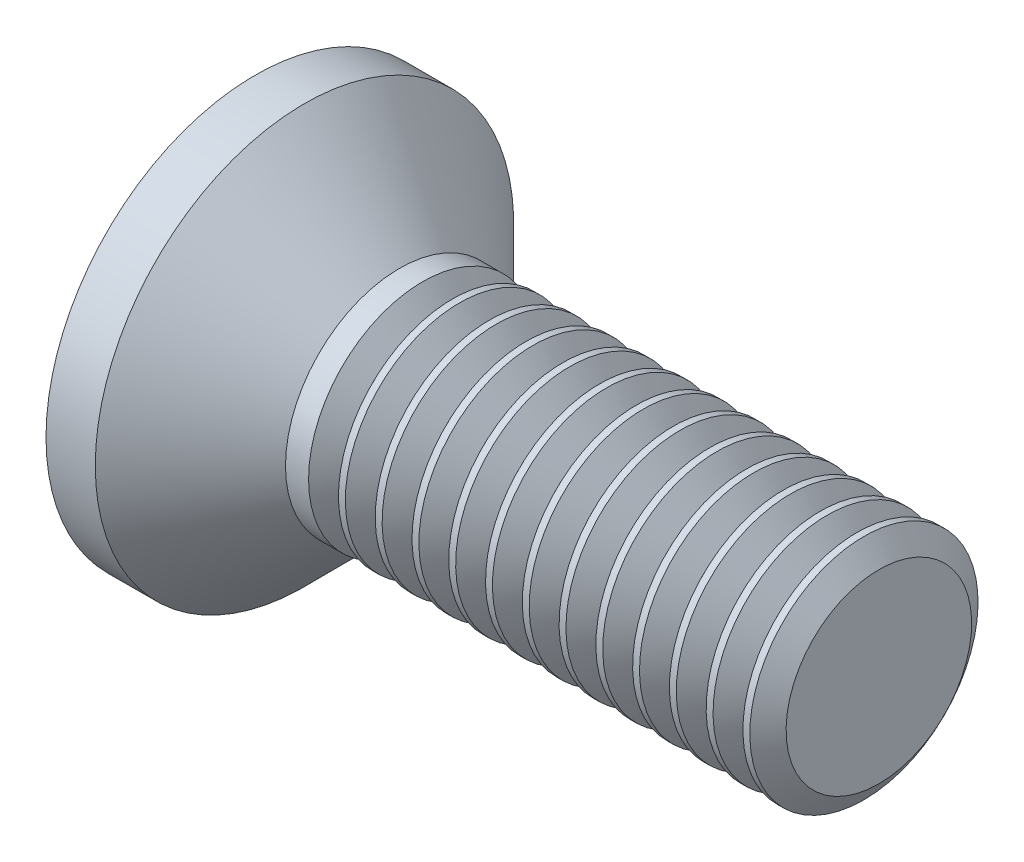
SolidWorks part; units mm, degrees
revolve "Base-Revolve" add sketch "BodySke" angle 360 about L4
sketch "BodySke" plane through (0, 0, 0) normal (0, 0, 1) x (1, 0, 0)
  line L0 (0, 0) -> (8.7277, 0)
  line L1 (8.7277, 0) -> (8.7277, 1.5)
  line L2 (8.7277, 1.5) -> (2.4277, 1.5)
  line L3 (2.4277, 1.5) -> (-7.1953, 11.123) construction
  line L4 (-15.875, 0) -> (82.55, 0) construction
  line L5 (2.4277, -1.5) -> (-7.1953, -11.123) construction
  line L6 (2.9277, 4.675) -> (2.9277, -11.2) construction
  line L7 (0.7277, 8.7375) -> (0.7277, -7.1375) construction
  line L8 (2.4277, 1.5) -> (1.1777, 2.75)
  line L9 (1.1777, 2.75) -> (0.53, 2.75)
  arc A0 (0, 0) -> (0.53, 2.75) centre (7.4, 0) cw
  arc A1 (0.7277, 3.2) -> (0, 0) centre (7.4, 0) ccw construction
  dimension "Crown_rad" = 7.4
  dimension "Diameter" = 3
  dimension "Advance" = 0.5
  dimension "Thread_nom" = 8
  dimension "Head_ang" = 90
  dimension "D3" = 6.4
  dimension "Side_ht" = 1.7
  dimension "D4" = 0.7277
  dimension "Length" = 8
  dimension "Head_dia" = 5.5
cosmetic thread "ThreadCosmetic" [suppressed] parameters "Thread_length"=5.8, "Thread_minor"=2.439
ref_plane "Plane1" through (0, 0, 0) normal (0, 0, 1) x (1, 0, 0)
ref_plane "Plane2" through (0, 0, 0) normal (0, 1, 0) x (1, 0, 0)
ref_plane "Plane3" through (0, 0, 0) normal (1, 0, 0) x (0, 0, -1)
sketch "Sketch2" plane through (0, 0, 0) normal (1, 0, 0) x (0, 0, -1)
  line L0 (2.75, -0.5) -> (-2.75, -0.5)
  line L1 (2.75, -0.5) -> (2.75, 0.5)
  line L2 (-2.75, 0.5) -> (2.75, 0.5)
  line L3 (-2.75, 0.5) -> (-2.75, -0.5)
  dimension "D1" = 5.5
  dimension "Slot_width" = 1
  dimension "D3" = 2.75
  dimension "D4" = 0.5
extrude "Slot" [suppressed] cut sketch "Sketch2" along normal blind 1.5
sketch "Sketch3" plane through (0, 0, 0) normal (1, 0, 0) x (0, 0, -1)
  line L0 (0.415, -1.72) -> (-0.415, -1.72)
  line L1 (0.415, -1.72) -> (0.415, 1.72)
  line L2 (-0.415, 1.72) -> (0.415, 1.72)
  line L3 (-0.415, 1.72) -> (-0.415, -1.72)
  dimension "Cross_width" = 0.83
  dimension "D1" = 0.415
  dimension "Cross_dia" = 3.44
  dimension "D2" = 1.72
ref_plane "Plane4" through (2.33, 0, 0) normal (1, 0, 0) x (0, 0, -1)
sketch "Sketch4" plane through (2.33, 0, 0) normal (1, 0, 0) x (0, 0, -1)
  line L0 (0.2075, -0.2075) -> (-0.2075, -0.2075)
  line L1 (0.2075, -0.2075) -> (0.2075, 0.2075)
  line L2 (-0.2075, 0.2075) -> (0.2075, 0.2075)
  line L3 (-0.2075, 0.2075) -> (-0.2075, -0.2075)
  dimension "D1" = 0.415
  dimension "D2" = 0.415
  dimension "D3" = 0.2075
  dimension "D4" = 0.2075
loft "Cross" cut profiles "Sketch3", "Sketch4"
pattern_circular "CirPattern1" count 2 every 90 about axis through (0, 0, 0) along (1, 0, 0) of "Cross"
sketch "ThdSchSke" plane through (0, 0, 0) normal (0, 0, 1) x (1, 0, 0)
  line L0 (2.9277, -1.2195) -> (2.7313, -1.5)
  line L1 (2.9277, -1.2195) -> (3.1241, -1.5)
  line L2 (3.1241, -1.5) -> (3.1241, -1.875)
  line L3 (-3.175, 0) -> (5.1513, 0) construction
  line L5 (3.1241, -1.875) -> (2.7313, -1.875)
  line L6 (2.7313, -1.875) -> (2.7313, -1.5)
  line L8 (8.7277, -1.5) -> (8.7277, 1.5) construction
  dimension "Diameter" = 3
  dimension "Thread_minor" = 2.439
  dimension "Start" = 5.8
revolve "ThreadSchematic" cut sketch "ThdSchSke" angle 360 about L3
pattern_linear "ThdSchPat" count 13 spacing 0.4833 along (1, 0, 0) of "ThreadSchematic"
equation "\"D1@Sketch2\" = \"Head_dia@BodySke\""
equation "\"D3@Sketch2\" = \"D1@Sketch2\" / 2"
equation "\"D4@Sketch2\" = \"Slot_width@Sketch2\" / 2"
equation "\"D1@Sketch3\" = \"Cross_width@Sketch3\" / 2"
equation "\"D2@Sketch3\" = \"Cross_dia@Sketch3\" / 2"
equation "\"D1@Sketch4\" = \"Cross_width@Sketch3\"*.5"
equation "\"D2@Sketch4\" = \"D1@Sketch4\""
equation "\"D3@Sketch4\" = \"D1@Sketch4\" / 2"
equation "\"D4@Sketch4\" = \"D2@Sketch4\" / 2"
equation "\"Thread_length@ThreadCosmetic\" = ((sgn( (\"Length@BodySke\" - \"Advance@BodySke\" - \"Side_ht@BodySke\" ) - \"Thread_nom@BodySke\" )-1)*( (\"Length@BodySke\" - \"Advance@BodySke\" - \"Side_ht@BodySke\" ) - \"Thread_nom@BodySke\" ))/-2+ \"Thread_nom@BodySke\""
equation "\"Thread_minor@ThdSchSke\" = \"Thread_minor@ThreadCosmetic\""
equation "\"Diameter@ThdSchSke\" = \"Diameter@BodySke\""
equation "\"Overcut@ThdSchSke\" = \"Diameter@BodySke\" * 1.25"
equation "\"Start@ThdSchSke\" =  \"Thread_length@ThreadCosmetic\""
equation "\"Num_threads@ThdSchPat\" = int( \"Thread_length@ThreadCosmetic\" / \"Advance@BodySke\" + 0.999 )  + 1"
equation "\"Advance@ThdSchPat\" = \"Thread_length@ThreadCosmetic\" /  (\"Num_threads@ThdSchPat\" - 1) 'relax it"
